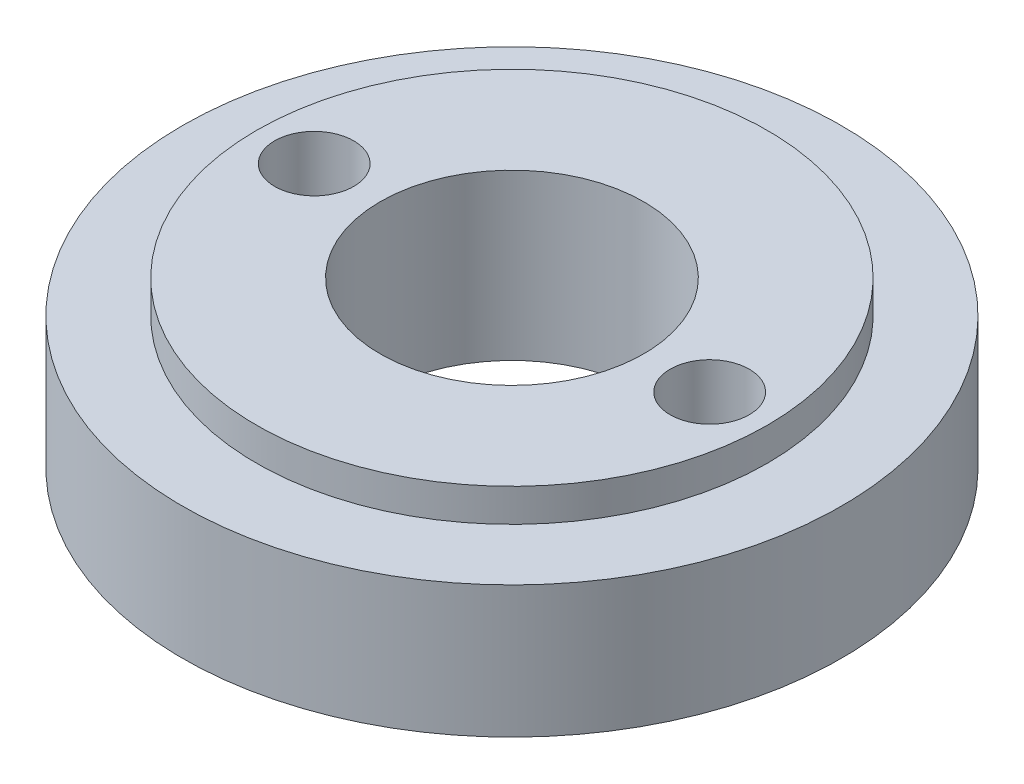
SolidWorks part; units mm, degrees
material "ABS"
ref_plane "Plan de face" through (0, 0, 0) normal (0, 0, 1) x (1, 0, 0)
ref_plane "Plan de dessus" through (0, 0, 0) normal (0, 1, 0) x (1, 0, 0)
ref_plane "Plan de droite" through (0, 0, 0) normal (1, 0, 0) x (0, 0, -1)
sketch "Esquisse1" plane through (0, 0, 0) normal (0, 0, 1) x (1, 0, 0)
  line L0 (0, 0) -> (0, -5) construction
  line L1 (4, 0) -> (4, -5)
  line L2 (4, -5) -> (10, -5)
  line L3 (10, -5) -> (10, -1)
  line L4 (10, -1) -> (7.75, -1)
  line L5 (7.75, -1) -> (7.75, 0)
  line L6 (7.75, 0) -> (4, 0)
  dimension "D1" = 1
  dimension "D2" = 4
  dimension "D3" = 8
  dimension "D4" = 15.5
  dimension "D5" = 20
revolve "Révolution1" add sketch "Esquisse1" angle 360 about L0
sketch "Esquisse2" plane through (0, 0, 0) normal (0, 1, 0) x (1, 0, 0)
  line L0 (-6, 0) -> (6, 0) construction
  circle A0 centre (6, 0) radius 1.2
  circle A1 centre (-6, 0) radius 1.2
  dimension "D1" = 12
  dimension "D2" = 2.4
extrude "Enlèv. mat.-Extru.1" cut sketch "Esquisse2" against normal through all
